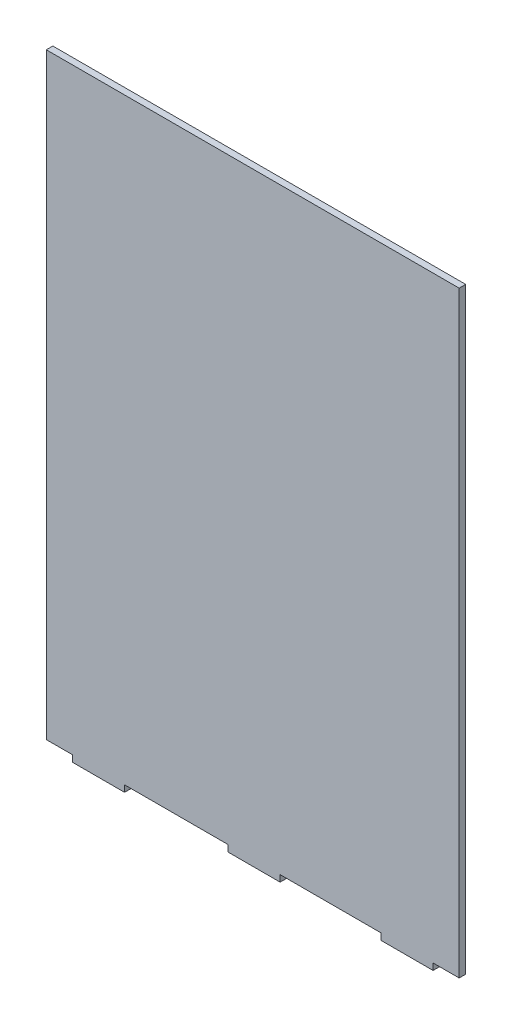
SolidWorks part; units mm, degrees
material "6061-T6 (SS)"
ref_plane "X-Y Datum" through (0, 0, 0) normal (0, 0, 1) x (1, 0, 0)
ref_plane "X-Z Datum" through (0, 0, 0) normal (0, 1, 0) x (1, 0, 0)
ref_plane "Y-Z Datum" through (0, 0, 0) normal (1, 0, 0) x (0, 0, -1)
sketch "Sketch1" plane through (0, 0, 0) normal (0, 0, 1) x (1, 0, 0)
  line L0 (0, 0) -> (0, -3.175) construction
  line L1 (0, 0) -> (12.7, 0)
  line L2 (0, 0) -> (0, 290.83)
  line L3 (0, 290.83) -> (200.98, 290.83)
  line L4 (200.98, 0) -> (200.98, 290.83)
  line L5 (0, -3.175) -> (12.7, -3.175) construction
  line L6 (101.1154, -1.5875) -> (38.1, -1.5875) construction
  line L7 (12.7, -3.175) -> (38.1, -3.175)
  line L8 (12.7, -3.175) -> (12.7, 0)
  line L10 (38.1, -3.175) -> (38.1, 0)
  line L11 (200.98, 0) -> (188.28, 0) construction
  line L12 (88.4154, -3.175) -> (113.8154, -3.175)
  line L13 (88.4154, -3.175) -> (88.4154, 0)
  line L15 (113.8154, -3.175) -> (113.8154, 0)
  line L16 (88.4154, -3.175) -> (113.8154, 0) construction
  line L17 (88.4154, 0) -> (113.8154, -3.175) construction
  line L23 (162.88, 0) -> (162.88, -3.175)
  line L24 (162.88, -3.175) -> (188.28, -3.175)
  line L25 (188.28, 0) -> (188.28, -3.175)
  line L26 (38.1, 0) -> (88.4154, 0)
  line L27 (113.8154, 0) -> (162.88, 0)
  line L28 (188.28, 0) -> (200.98, 0)
  dimension "D1" = 25.4
  dimension "D2" = 25.4
  dimension "D3" = 12.7
  dimension "D4" = 3.175
  dimension "D5" = 25.4
  dimension "D6" = 3.175
extrude "Boss-Extrude1" add sketch "Sketch1" along normal blind 3.175
